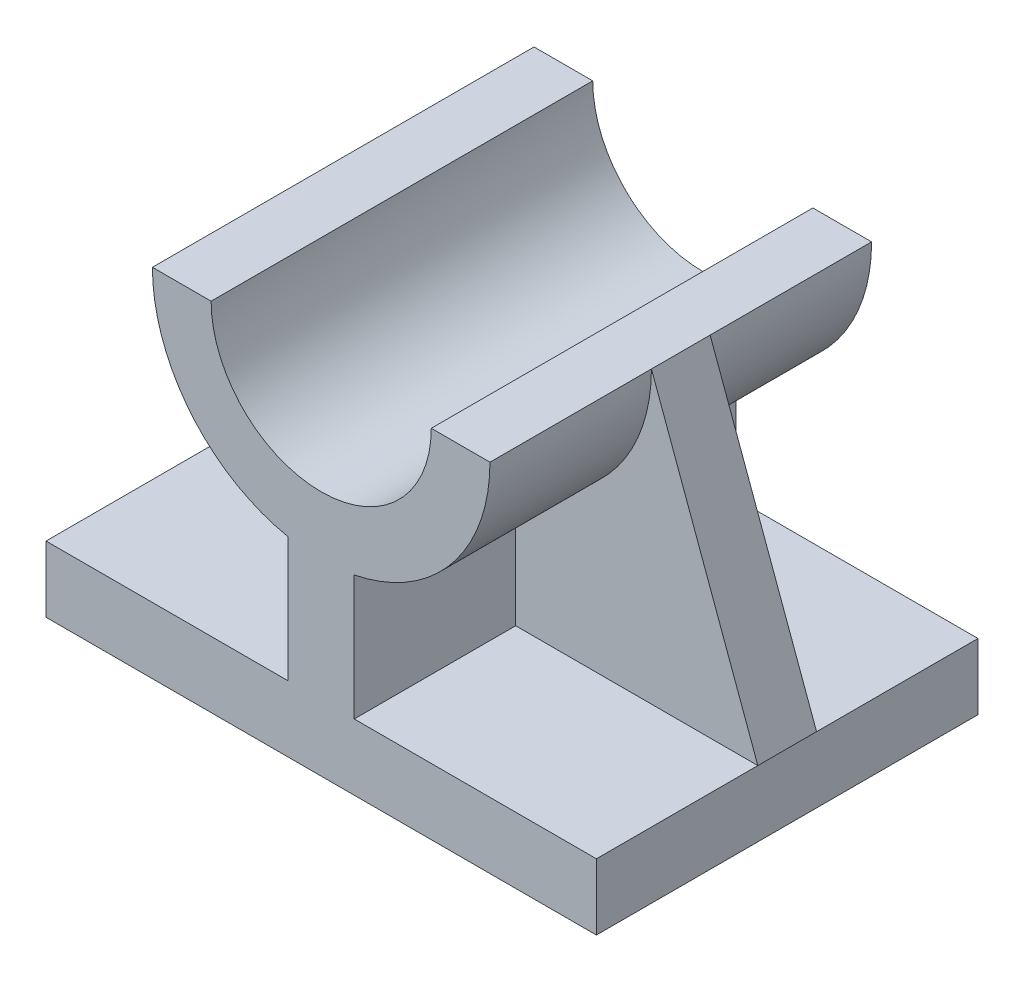
SolidWorks part; units mm, degrees
ref_plane "Front Plane" through (0, 0, 0) normal (0, 0, 1) x (1, 0, 0)
ref_plane "Top Plane" through (0, 0, 0) normal (0, 1, 0) x (1, 0, 0)
ref_plane "Right Plane" through (0, 0, 0) normal (1, 0, 0) x (0, 0, -1)
sketch "Sketch1" plane through (0, 0, 0) normal (0, 1, 0) x (1, 0, 0)
  line L1 (-37.5, 26) -> (37.5, 26)
  line L2 (-37.5, 26) -> (-37.5, -26)
  line L3 (-37.5, -26) -> (37.5, -26)
  line L4 (37.5, 26) -> (37.5, -26)
  line L5 (-37.5, 26) -> (37.5, -26) construction
  line L6 (-37.5, -26) -> (37.5, 26) construction
  point P0 (0, 0)
  dimension "D1" = 75
  dimension "D2" = 52
extrude "Boss-Extrude1" add sketch "Sketch1" along normal blind 9
sketch "Sketch2" plane through (0, 0, 26) normal (0, 0, 1) x (1, 0, 0)
  line L0 (0, 31.441) -> (0, -29.1178) construction
  line L1 (-4.5, 9) -> (-4.5, 26)
  line L2 (-37.5, 9) -> (37.5, 9) construction
  line L3 (4.5, 9) -> (4.5, 26)
  line L4 (-59.2579, 48.5555) -> (79.5989, 48.5555) construction
  line L5 (15, 48.5555) -> (23, 48.5555)
  line L6 (-15, 48.5555) -> (-23, 48.5555)
  line L7 (-4.5, 9) -> (4.5, 9)
  arc A0 (-23, 48.5555) -> (23, 48.5555) centre (0, 48.5555) ccw
  arc A1 (-15, 48.5555) -> (15, 48.5555) centre (0, 48.5555) ccw
  point P7 (0, 0)
  dimension "D3" = 23
  dimension "D4" = 15
  dimension "D1" = 4.5
  dimension "D2" = 17
extrude "Boss-Extrude2" add sketch "Sketch2" against normal blind 52 contours A1 L6 A0 L5 | A0 L1 L4 L3
sketch "Sketch3" plane through (0, 0, 0) normal (0, 0, 1) x (1, 0, 0)
  line L0 (4.5, 9) -> (37.5, 9)
  line L1 (37.5, 9) -> (23, 48.5555)
  line L2 (4.5, 26) -> (4.5, 9)
  arc A0 (4.5, 26) -> (23, 48.5555) centre (0, 48.5555) ccw
extrude "Boss-Extrude3" add sketch "Sketch3" along normal blind 4 and the other way blind 4
